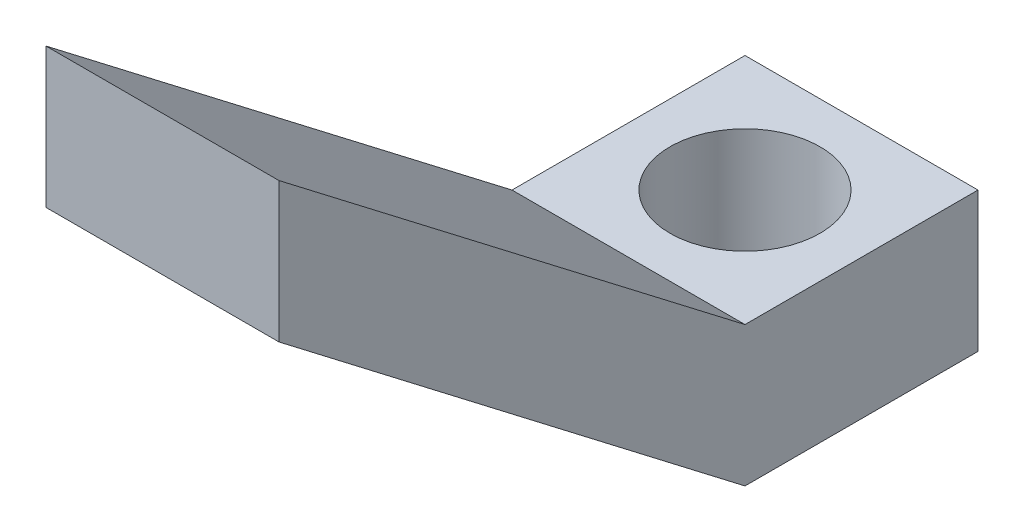
SolidWorks part; units mm, degrees
ref_plane "前视基准面" through (0, 0, 0) normal (0, 0, 1) x (1, 0, 0)
ref_plane "上视基准面" through (0, 0, 0) normal (0, 1, 0) x (1, 0, 0)
ref_plane "右视基准面" through (0, 0, 0) normal (1, 0, 0) x (0, 0, -1)
other "Configuration Table"
sketch "草图1" plane through (0, 0, 0) normal (0, 1, 0) x (1, 0, 0)
  line L1 (-12.5, -12.5) -> (12.5, -12.5)
  line L2 (-12.5, -12.5) -> (-12.5, 12.5)
  line L3 (-12.5, 12.5) -> (12.5, 12.5)
  line L4 (12.5, -12.5) -> (12.5, 12.5)
  line L5 (-12.5, -12.5) -> (12.5, 12.5) construction
  line L6 (-12.5, 12.5) -> (12.5, -12.5) construction
  point P0 (0, 0)
  dimension "D1" = 25
  dimension "D2" = 25
extrude "凸台-拉伸1" add sketch "草图1" along normal blind 15
sketch "草图2" plane through (0, 15, 0) normal (0, 1, 0) x (1, 0, 0)
  circle A0 centre (0, 0) radius 8.05
  dimension "D1" = 16.1
extrude "切除-拉伸1" cut sketch "草图2" against normal through all
sketch "草图3" plane through (-12.5, 0, 0) normal (-1, 0, 0) x (0, 0, 1)
  line L3 (12.5, 15) -> (62.5, 53.3793)
  line L6 (12.5, 15) -> (12.5, 0)
  line L7 (12.5, 0) -> (62.5, 38.3793)
  line L8 (62.5, 38.3793) -> (62.5, 53.3793)
  dimension "D1" = 50
extrude "凸台-拉伸2" add sketch "草图3" against normal blind 25
